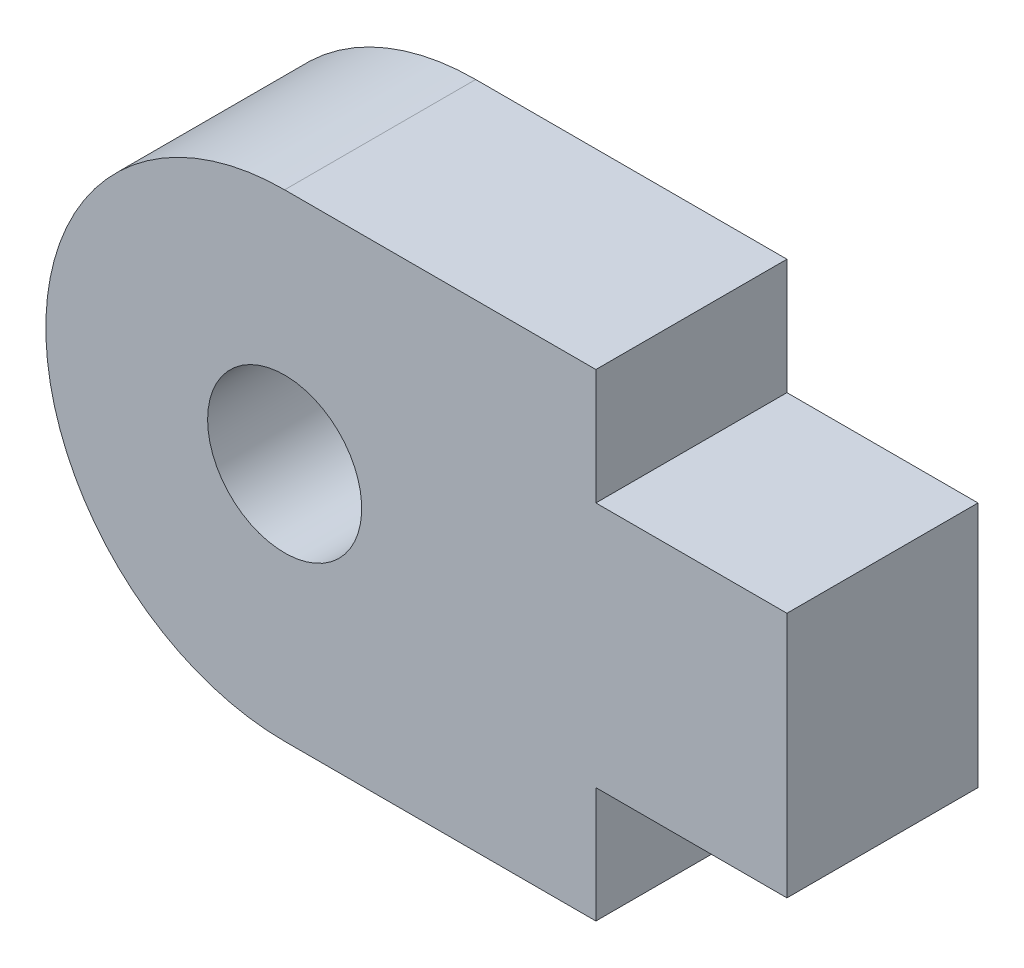
SolidWorks part; units mm, degrees
ref_plane "Front Plane" through (0, 0, 0) normal (0, 0, 1) x (1, 0, 0)
ref_plane "Top Plane" through (0, 0, 0) normal (0, 1, 0) x (1, 0, 0)
ref_plane "Right Plane" through (0, 0, 0) normal (1, 0, 0) x (0, 0, -1)
sketch "Sketch1" plane through (0, 0, 0) normal (0, 0, 1) x (1, 0, 0)
  line L0 (-19.1918, 13.2667) -> (-19.1918, 11.3917)
  line L1 (-19.1918, 7.3917) -> (-19.1918, 5.5167)
  line L2 (-22.2918, 13.2667) -> (-22.2918, 5.5618) construction
  line L3 (-24.2418, 13.2667) -> (-19.1918, 13.2667)
  line L4 (-19.1918, 5.5167) -> (-24.2418, 5.5167)
  line L6 (-19.1918, 7.3917) -> (-16.0918, 7.3917)
  line L7 (-19.1918, 11.3917) -> (-16.0918, 11.3917)
  line L8 (-16.0918, 7.3917) -> (-16.0918, 11.3917)
  circle A8 centre (-24.2418, 9.4143) radius 1.25
  arc A12 (-24.2418, 13.2667) -> (-24.2418, 5.5167) centre (-24.2418, 9.3917) ccw
  dimension "D1" = 3.1
extrude "Extrude1" add sketch "Sketch1" along normal blind 3.1
